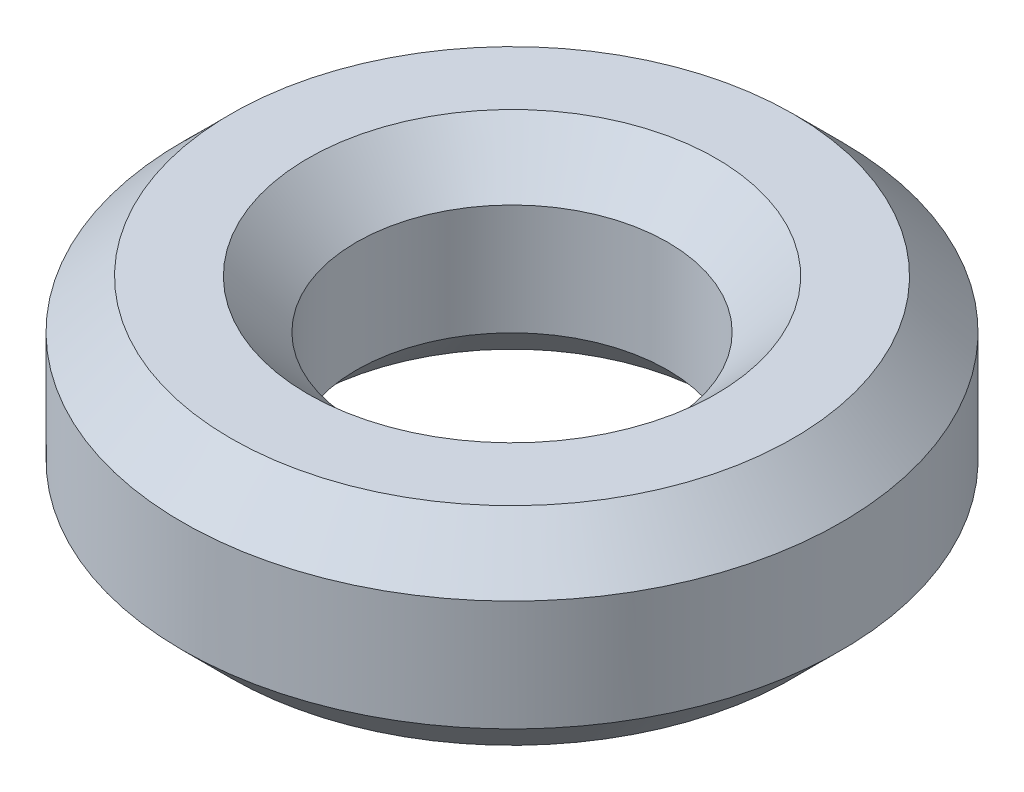
SolidWorks part; units mm, degrees
ref_plane "Front Plane" through (0, 0, 0) normal (0, 0, 1) x (1, 0, 0)
ref_plane "Top Plane" through (0, 0, 0) normal (0, 1, 0) x (1, 0, 0)
ref_plane "Right Plane" through (0, 0, 0) normal (1, 0, 0) x (0, 0, -1)
sketch "Sketch1" plane through (0, 0, 0) normal (0, 1, 0) x (1, 0, 0)
  circle A0 centre (0, 0) radius 2.25
  circle A1 centre (0, 0) radius 4.7625
  circle A2 centre (0, 0) radius 4.7625 construction
  dimension "D1" = 4.5
extrude "Boss-Extrude1" add sketch "Sketch1" along normal blind 3
chamfer "Chamfer1" distance 0.7 angle 45 4 edges at (0, 0, 2.25) (0, 0, 4.7625) (0, 3, 2.25) (0, 3, 4.7625)
